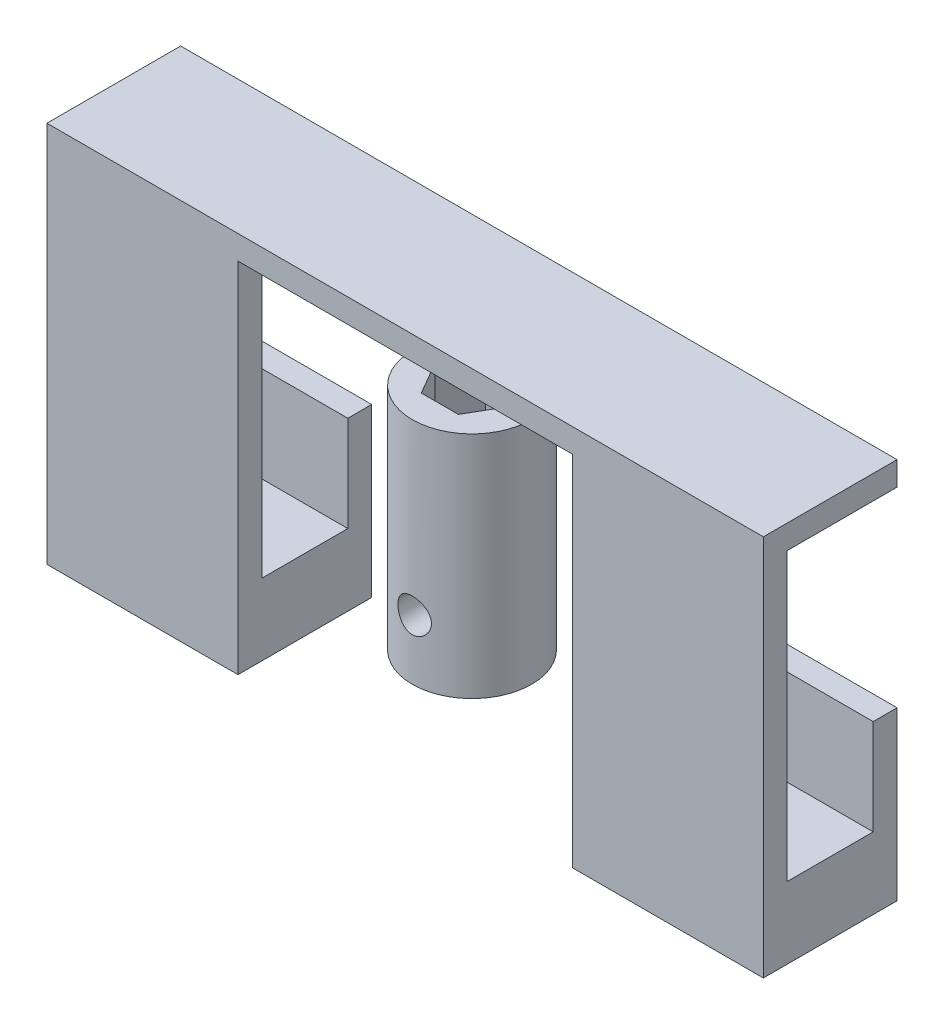
SolidWorks part; units mm, degrees
ref_plane "Front Plane" through (0, 0, 0) normal (0, 0, 1) x (1, 0, 0)
ref_plane "Top Plane" through (0, 0, 0) normal (0, 1, 0) x (1, 0, 0)
ref_plane "Right Plane" through (0, 0, 0) normal (1, 0, 0) x (0, 0, -1)
sketch "Sketch2" plane through (0, 0, 0) normal (0, 1, 0) x (1, 0, 0)
  line L0 (0, 0) -> (0, 29.7103) construction
  line L1 (-37.5, 0) -> (-17.5, 0)
  line L2 (-37.5, 0) -> (-37.5, 14)
  line L3 (-37.5, 14) -> (-17.5, 14)
  line L4 (-17.5, 0) -> (-17.5, 14)
  line L5 (0, -16.3407) -> (0, 16.3407) construction
  line L14 (37.5, 14) -> (17.5, 14)
  line L15 (17.5, 0) -> (17.5, 14)
  line L16 (37.5, 0) -> (17.5, 0)
  line L17 (37.5, 0) -> (37.5, 14)
  dimension "D1" = 17.5
  dimension "D2" = 14
  dimension "D3" = 20
extrude "Boss-Extrude1" add sketch "Sketch2" against normal blind 7.5 contours L2 L1 L4 L3
sketch "Sketch4" plane through (0, 0, 0) normal (0, 1, 0) x (1, 0, 0)
  line L0 (-17.5, 0) -> (-17.5, 14) construction
  line L1 (-37.5, 14) -> (-17.5, 14)
  line L2 (-37.5, 14) -> (-37.5, 11.5)
  line L3 (-37.5, 11.5) -> (-17.5, 11.5)
  line L4 (-17.5, 14) -> (-17.5, 11.5)
  line L6 (-37.5, 0) -> (-17.5, 0)
  line L7 (-37.5, 0) -> (-37.5, 2.5)
  line L8 (-37.5, 2.5) -> (-17.5, 2.5)
  line L9 (-17.5, 0) -> (-17.5, 2.5)
  dimension "D1" = 2.5
  dimension "D2" = 2.5
extrude "Boss-Extrude2" add sketch "Sketch4" along normal blind 10 contours L2 L1 L4 L3
sketch "Sketch6" plane through (0, 0, 0) normal (0, 1, 0) x (1, 0, 0)
  line L0 (-17.5, 0) -> (-17.5, 11.5) construction
  line L1 (-37.5, 0) -> (-17.5, 0)
  line L2 (-37.5, 0) -> (-37.5, 2.5)
  line L3 (-37.5, 2.5) -> (-17.5, 2.5)
  line L4 (-17.5, 0) -> (-17.5, 2.5)
  dimension "D1" = 2.5
extrude "Boss-Extrude3" add sketch "Sketch6" along normal blind 30
sketch "Sketch8" plane through (0, 0, 0) normal (0, 1, 0) x (1, 0, 0)
  line L1 (17.5, 0) -> (37.5, 0)
  line L2 (17.5, 0) -> (17.5, 14)
  line L3 (17.5, 14) -> (37.5, 14)
  line L4 (37.5, 0) -> (37.5, 14)
  dimension "D1" = 17.5
  dimension "D2" = 14
  dimension "D3" = 20
extrude "Boss-Extrude4" add sketch "Sketch8" against normal blind 7.5 separate body contours L2 L1 L4 L3
sketch "Sketch9" plane through (0, 0, 0) normal (0, 1, 0) x (1, 0, 0)
  line L0 (37.5, 0) -> (37.5, 14) construction
  line L1 (17.5, 14) -> (37.5, 14)
  line L2 (17.5, 14) -> (17.5, 11.5)
  line L3 (17.5, 11.5) -> (37.5, 11.5)
  line L4 (37.5, 14) -> (37.5, 11.5)
  dimension "D1" = 2.5
extrude "Boss-Extrude5" add sketch "Sketch9" along normal blind 10
sketch "Sketch10" plane through (0, 0, 0) normal (0, 1, 0) x (1, 0, 0)
  line L0 (-22, 0) -> (22, 0) construction
  line L1 (17.5, 0) -> (37.5, 0)
  line L2 (17.5, 0) -> (17.5, 2.5)
  line L3 (17.5, 2.5) -> (37.5, 2.5)
  line L4 (37.5, 0) -> (37.5, 2.5)
  line L5 (17.5, 0) -> (17.5, 11.5) construction
  line L6 (37.5, 0) -> (37.5, 11.5) construction
  dimension "D1" = 2.5
extrude "Boss-Extrude6" add sketch "Sketch10" along normal blind 30
sketch "Sketch11" plane through (0, 30, 0) normal (0, 1, 0) x (1, 0, 0)
  line L1 (-37.5, 0) -> (37.5, 0)
  line L2 (-37.5, 0) -> (-37.5, 14)
  line L3 (-37.5, 14) -> (37.5, 14)
  line L4 (37.5, 0) -> (37.5, 14)
extrude "Boss-Extrude7" add sketch "Sketch11" along normal blind 2.5
sketch "Sketch12" plane through (0, 32.5, 0) normal (0, 1, 0) x (1, 0, 0)
  line L0 (0, 0) -> (0, 15.2712) construction
  line L1 (0, -7.7) -> (0, 7.7) construction
  line L2 (37.5, 14) -> (-37.5, 14) construction
  line L3 (-1.9442, 10.3675) -> (-3.8885, 7)
  line L4 (-3.8885, 7) -> (-1.9442, 3.6325)
  line L5 (-1.9442, 3.6325) -> (1.9442, 3.6325)
  line L6 (1.9442, 3.6325) -> (3.8885, 7)
  line L7 (3.8885, 7) -> (1.9442, 10.3675)
  line L8 (1.9442, 10.3675) -> (-1.9442, 10.3675)
  line L11 (-37.5, 14) -> (-37.5, 0) construction
  circle A0 centre (0, 7) radius 3.3675 construction
  circle A1 centre (0, 7) radius 6.25
  dimension "D4" = 12.5
  dimension "D1" = 6.735
  dimension "D2" = 7
  dimension "D3" = 37.5
extrude "Boss-Extrude8" add sketch "Sketch12" along normal blind 24 from surface at -32.5 starting at plane "Top Plane"
ref_plane "Plane1" through (0, 6.254, 0) normal (0, 1, 0) x (1, 0, 0)
sketch "Sketch13" plane through (0, 0, 0) normal (0, 0, 1) x (1, 0, 0)
  line L0 (6.875, 6.254) -> (-6.875, 6.254) construction
  line L1 (0, -7.7) -> (0, 7.7) construction
  circle A0 centre (0, 6.254) radius 1.752
  dimension "D1" = 3.5041
extrude "Cut-Extrude1" cut sketch "Sketch13" against normal through all
ref_plane "Plane2" through (0, 24, 0) normal (0, 1, 0) x (1, 0, 0)
sketch "Sketch14" plane through (0, 24, 0) normal (0, 1, 0) x (1, 0, 0)
  line L1 (-56.0284, -31.1063) -> (57.2469, -31.1063)
  line L2 (-56.0284, -31.1063) -> (-56.0284, 42.8936)
  line L3 (-56.0284, 42.8936) -> (57.2469, 42.8936)
  line L4 (57.2469, -31.1063) -> (57.2469, 42.8936)
  line L5 (-56.0284, -31.1063) -> (57.2469, 42.8936) construction
  line L6 (-56.0284, 42.8936) -> (57.2469, -31.1063) construction
  point P0 (0.6093, 5.8937)
